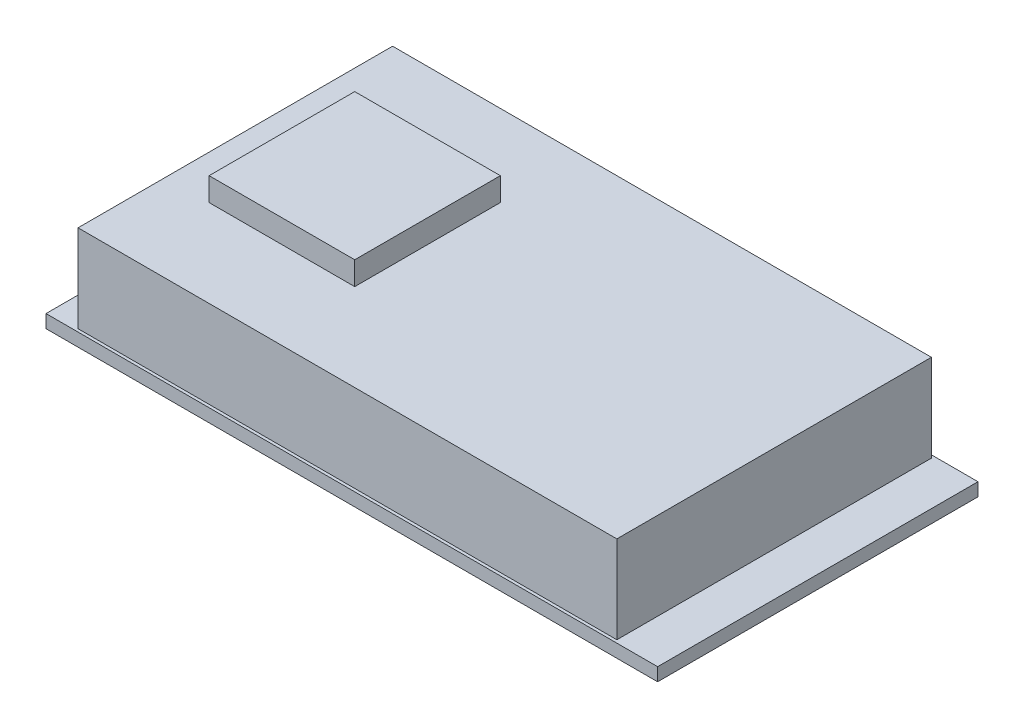
SolidWorks part; units mm, degrees
ref_plane "Front Plane" through (0, 0, 0) normal (0, 0, 1) x (1, 0, 0)
ref_plane "Top Plane" through (0, 0, 0) normal (0, 1, 0) x (1, 0, 0)
ref_plane "Right Plane" through (0, 0, 0) normal (1, 0, 0) x (0, 0, -1)
sketch "Sketch1" plane through (0, 0, 0) normal (0, 1, 0) x (1, 0, 0)
  line L1 (-105, 55) -> (105, 55)
  line L2 (-105, 55) -> (-105, -55)
  line L3 (-105, -55) -> (105, -55)
  line L4 (105, 55) -> (105, -55)
  line L5 (-105, 55) -> (105, -55) construction
  line L6 (-105, -55) -> (105, 55) construction
  point P0 (0, 0)
  dimension "D1" = 110
  dimension "D2" = 210
extrude "Boss-Extrude1" add sketch "Sketch1" along normal blind 4.5
sketch "Sketch2" plane through (0, 4.5, 0) normal (0, 1, 0) x (1, 0, 0)
  line L0 (105, -55) -> (105, 55) construction
  line L1 (90, 54) -> (-95, 54)
  line L2 (90, 54) -> (90, -54)
  line L3 (90, -54) -> (-95, -54)
  line L4 (-95, 54) -> (-95, -54)
  line L5 (-105, 55) -> (-105, -55) construction
  line L8 (105, 55) -> (-105, 55) construction
  line L9 (-105, -55) -> (105, -55) construction
  dimension "D1" = 15
  dimension "D2" = 10
  dimension "D3" = 1
  dimension "D4" = 1
extrude "Boss-Extrude2" add sketch "Sketch2" along normal blind 30
sketch "Sketch3" plane through (0, 34.5, 0) normal (0, 1, 0) x (1, 0, 0)
  line L0 (90, 54) -> (-95, 54) construction
  line L1 (-80, 26) -> (-30, 26)
  line L2 (-80, 26) -> (-80, -24)
  line L3 (-80, -24) -> (-30, -24)
  line L4 (-30, 26) -> (-30, -24)
  line L5 (-95, -54) -> (90, -54) construction
  line L6 (-95, 54) -> (-95, -54) construction
  dimension "D1" = 15
  dimension "D2" = 50
  dimension "D3" = 50
  dimension "D4" = 30
  dimension "D5" = 28
extrude "Boss-Extrude3" add sketch "Sketch3" along normal blind 8 contours L1 L4 L3 L2
